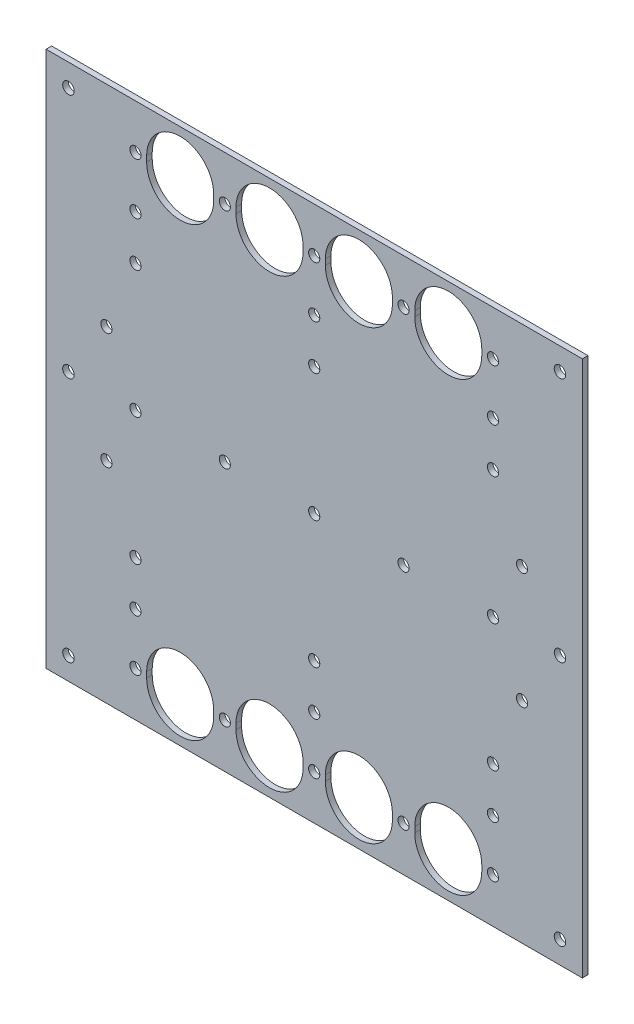
SolidWorks part; units mm, degrees
ref_plane "Front Plane" through (0, 0, 0) normal (0, 0, 1) x (1, 0, 0)
ref_plane "Top Plane" through (0, 0, 0) normal (0, 1, 0) x (1, 0, 0)
ref_plane "Right Plane" through (0, 0, 0) normal (1, 0, 0) x (0, 0, -1)
sketch "Sketch1" plane through (0, 0, 0) normal (0, 0, 1) x (1, 0, 0)
  line L0 (-152.4, 127) -> (-76.2, 127) construction
  line L1 (-152.4, 152.4) -> (152.4, 152.4)
  line L2 (-152.4, 152.4) -> (-152.4, -152.4)
  line L3 (-152.4, -152.4) -> (152.4, -152.4)
  line L4 (152.4, 152.4) -> (152.4, -152.4)
  line L5 (-76.2, 127) -> (-25.4, 127) construction
  line L6 (-25.4, 127) -> (25.4, 127) construction
  line L7 (25.4, 127) -> (76.2, 127) construction
  line L8 (76.2, 127) -> (152.4, 127) construction
  line L9 (-152.4, 0) -> (152.4, 0) construction
  line L10 (0, 152.4) -> (0, -152.4) construction
  line L11 (-118.11, 152.4) -> (-118.11, -152.4) construction
  line L12 (-152.4, -127) -> (152.4, -127) construction
  line L13 (127, 152.4) -> (127, -152.4) construction
  line L14 (-50.8, 152.4) -> (-50.8, -152.4) construction
  line L15 (50.8, 152.4) -> (50.8, -152.4) construction
  line L16 (-101.6, 152.4) -> (-101.6, -152.4) construction
  line L17 (-95.25, 66.04) -> (-57.15, 66.04) construction
  line L18 (-95.25, 66.04) -> (-95.25, -66.04) construction
  line L19 (-95.25, -66.04) -> (-57.15, -66.04) construction
  line L20 (-57.15, 66.04) -> (-57.15, -66.04) construction
  line L21 (-44.45, 66.04) -> (-6.35, 66.04) construction
  line L22 (-44.45, 66.04) -> (-44.45, -66.04) construction
  line L23 (-44.45, -66.04) -> (-6.35, -66.04) construction
  line L24 (-6.35, 66.04) -> (-6.35, -66.04) construction
  line L25 (6.35, 66.04) -> (44.45, 66.04) construction
  line L26 (6.35, 66.04) -> (6.35, -66.04) construction
  line L27 (6.35, -66.04) -> (44.45, -66.04) construction
  line L28 (44.45, 66.04) -> (44.45, -66.04) construction
  line L29 (57.15, 66.04) -> (95.25, 66.04) construction
  line L30 (57.15, 66.04) -> (57.15, -66.04) construction
  line L31 (57.15, -66.04) -> (95.25, -66.04) construction
  line L32 (95.25, 66.04) -> (95.25, -66.04) construction
  line L33 (101.6, 152.4) -> (101.6, -152.4) construction
  line L34 (-152.4, 120.65) -> (152.4, 120.65) construction
  line L35 (-101.6, 39.7057) -> (-95.25, 39.7057) construction
  line L36 (-57.15, 39.7057) -> (-50.8, 39.7057) construction
  line L37 (-76.2, 66.04) -> (-76.2, 0) construction
  line L38 (-76.2, 0) -> (-76.2, -66.04) construction
  line L39 (-152.4, 72.39) -> (152.4, 72.39) construction
  line L40 (-152.4, -72.39) -> (152.4, -72.39) construction
  line L41 (-76.2, 66.04) -> (-76.2, 72.39) construction
  line L42 (-95.25, -66.04) -> (-95.25, -72.39) construction
  line L43 (95.25, 39.7057) -> (101.6, 39.7057) construction
  line L44 (-95.25, 111.76) -> (-57.15, 111.76) construction
  line L45 (-57.15, 111.76) -> (-57.15, 118.4779) construction
  line L46 (-94.0266, 120.65) -> (-78.1749, 130.2582) construction
  line L47 (-95.25, 111.76) -> (-95.25, 118.4779) construction
  line L48 (-58.3734, 120.65) -> (-74.2251, 130.2582) construction
  line L49 (-107.3169, 130.81) -> (-83.1894, 130.81) construction
  line L50 (-6.35, 111.76) -> (-6.35, 118.4779) construction
  line L51 (-7.5734, 120.65) -> (-23.4251, 130.2582) construction
  line L52 (-43.2266, 120.65) -> (-27.3749, 130.2582) construction
  line L53 (-44.45, 111.76) -> (-44.45, 118.4779) construction
  line L54 (-6.35, 111.76) -> (-44.45, 111.76) construction
  line L55 (44.45, 111.76) -> (44.45, 118.4779) construction
  line L56 (43.2266, 120.65) -> (27.3749, 130.2582) construction
  line L57 (7.5734, 120.65) -> (23.4251, 130.2582) construction
  line L58 (6.35, 111.76) -> (6.35, 118.4779) construction
  line L59 (6.35, 111.76) -> (44.45, 111.76) construction
  line L60 (95.25, 111.76) -> (57.15, 111.76) construction
  line L61 (95.25, 111.76) -> (95.25, 118.4779) construction
  line L62 (94.0266, 120.65) -> (78.1749, 130.2582) construction
  line L63 (58.3734, 120.65) -> (74.2251, 130.2582) construction
  line L64 (57.15, 111.76) -> (57.15, 118.4779) construction
  line L65 (-95.25, -111.76) -> (-95.25, -118.4779) construction
  line L66 (-94.0266, -120.65) -> (-78.1749, -130.2582) construction
  line L67 (-58.3734, -120.65) -> (-74.2251, -130.2582) construction
  line L68 (-95.25, -111.76) -> (-57.15, -111.76) construction
  line L69 (-57.15, -111.76) -> (-57.15, -118.4779) construction
  line L70 (-44.45, -111.76) -> (-44.45, -118.4779) construction
  line L71 (-43.2266, -120.65) -> (-27.3749, -130.2582) construction
  line L72 (-6.35, -111.76) -> (-44.45, -111.76) construction
  line L73 (-7.5734, -120.65) -> (-23.4251, -130.2582) construction
  line L74 (-6.35, -111.76) -> (-6.35, -118.4779) construction
  line L75 (6.35, -111.76) -> (6.35, -118.4779) construction
  line L76 (7.5734, -120.65) -> (23.4251, -130.2582) construction
  line L77 (43.2266, -120.65) -> (27.3749, -130.2582) construction
  line L78 (6.35, -111.76) -> (44.45, -111.76) construction
  line L79 (44.45, -111.76) -> (44.45, -118.4779) construction
  line L80 (57.15, -111.76) -> (57.15, -118.4779) construction
  line L81 (58.3734, -120.65) -> (74.2251, -130.2582) construction
  line L82 (94.0266, -120.65) -> (78.1749, -130.2582) construction
  line L83 (95.25, -111.76) -> (57.15, -111.76) construction
  line L84 (95.25, -111.76) -> (95.25, -118.4779) construction
  line L85 (-152.4, 97.79) -> (152.4, 97.79) construction
  line L86 (-50.8, 39.7057) -> (-44.45, 39.7057) construction
  line L87 (-127, 152.4) -> (-127, -152.4) construction
  line L89 (-95.25, 101.6) -> (-92.3192, 101.6) construction
  line L90 (-95.25, 101.6) -> (-95.25, -101.6) construction
  line L96 (-90.8538, 101.6) -> (-90.8538, 68.58) construction
  line L97 (-89.3885, 101.6) -> (-89.3885, 68.58) construction
  line L98 (-92.3192, 101.6) -> (-92.3192, 68.58) construction
  line L99 (-83.5269, 101.6) -> (-83.5269, 68.58) construction
  line L100 (-86.4577, 101.6) -> (-86.4577, 68.58) construction
  line L101 (-89.3885, 101.6) -> (-86.4577, 101.6) construction
  line L102 (-77.6654, 101.6) -> (-77.6654, 68.58) construction
  line L103 (-80.5962, 101.6) -> (-80.5962, 68.58) construction
  line L104 (-83.5269, 101.6) -> (-80.5962, 101.6) construction
  line L105 (-71.8038, 101.6) -> (-71.8038, 68.58) construction
  line L106 (-74.7346, 101.6) -> (-74.7346, 68.58) construction
  line L107 (-77.6654, 101.6) -> (-74.7346, 101.6) construction
  line L108 (-65.9423, 101.6) -> (-65.9423, 68.58) construction
  line L109 (-68.8731, 101.6) -> (-68.8731, 68.58) construction
  line L110 (-71.8038, 101.6) -> (-68.8731, 101.6) construction
  line L111 (-60.0808, 101.6) -> (-60.0808, 68.58) construction
  line L112 (-63.0115, 101.6) -> (-63.0115, 68.58) construction
  line L113 (-65.9423, 101.6) -> (-63.0115, 101.6) construction
  line L114 (-57.15, -101.6) -> (-57.15, 101.6) construction
  line L115 (-60.0808, 101.6) -> (-57.15, 101.6) construction
  line L116 (-92.3192, 68.58) -> (-89.3885, 68.58) construction
  line L117 (-60.0808, -101.6) -> (-57.15, -101.6) construction
  line L118 (-60.0808, -101.6) -> (-60.0808, -68.58) construction
  line L119 (-63.0115, -101.6) -> (-63.0115, -68.58) construction
  line L120 (-65.9423, -101.6) -> (-65.9423, -68.58) construction
  line L121 (-65.9423, -101.6) -> (-63.0115, -101.6) construction
  line L122 (-68.8731, -101.6) -> (-68.8731, -68.58) construction
  line L123 (-71.8038, -101.6) -> (-68.8731, -101.6) construction
  line L124 (-71.8038, -101.6) -> (-71.8038, -68.58) construction
  line L125 (-74.7346, -101.6) -> (-74.7346, -68.58) construction
  line L126 (-77.6654, -101.6) -> (-74.7346, -101.6) construction
  line L127 (-77.6654, -101.6) -> (-77.6654, -68.58) construction
  line L128 (-80.5962, -101.6) -> (-80.5962, -68.58) construction
  line L129 (-83.5269, -101.6) -> (-80.5962, -101.6) construction
  line L130 (-83.5269, -101.6) -> (-83.5269, -68.58) construction
  line L131 (-86.4577, -101.6) -> (-86.4577, -68.58) construction
  line L132 (-89.3885, -101.6) -> (-86.4577, -101.6) construction
  line L133 (-89.3885, -101.6) -> (-89.3885, -68.58) construction
  line L134 (-92.3192, -101.6) -> (-92.3192, -68.58) construction
  line L135 (-95.25, -101.6) -> (-92.3192, -101.6) construction
  line L136 (-9.2808, 68.58) -> (-12.2115, 68.58) construction
  line L137 (6.35, 66.04) -> (44.45, 66.04) construction
  line L138 (-6.35, -66.04) -> (-6.35, -72.39) construction
  line L139 (-25.4, 66.04) -> (-25.4, 72.39) construction
  line L140 (-25.4, 0) -> (-25.4, -66.04) construction
  line L141 (-25.4, 66.04) -> (-25.4, 0) construction
  line L142 (-44.45, 66.04) -> (-44.45, -66.04) construction
  line L143 (-6.35, -66.04) -> (-44.45, -66.04) construction
  line L144 (-6.35, 66.04) -> (-6.35, -66.04) construction
  line L145 (-6.35, 66.04) -> (-44.45, 66.04) construction
  line L146 (-6.35, -101.6) -> (-9.2808, -101.6) construction
  line L147 (-9.2808, -101.6) -> (-9.2808, -68.58) construction
  line L148 (-12.2115, -101.6) -> (-12.2115, -68.58) construction
  line L149 (-12.2115, -101.6) -> (-15.1423, -101.6) construction
  line L150 (-15.1423, -101.6) -> (-15.1423, -68.58) construction
  line L151 (-18.0731, -101.6) -> (-18.0731, -68.58) construction
  line L152 (-18.0731, -101.6) -> (-21.0038, -101.6) construction
  line L153 (-21.0038, -101.6) -> (-21.0038, -68.58) construction
  line L154 (-23.9346, -101.6) -> (-23.9346, -68.58) construction
  line L155 (-23.9346, -101.6) -> (-26.8654, -101.6) construction
  line L156 (-26.8654, -101.6) -> (-26.8654, -68.58) construction
  line L157 (-29.7962, -101.6) -> (-29.7962, -68.58) construction
  line L158 (-29.7962, -101.6) -> (-32.7269, -101.6) construction
  line L159 (-32.7269, -101.6) -> (-32.7269, -68.58) construction
  line L160 (-35.6577, -101.6) -> (-38.5885, -101.6) construction
  line L161 (-35.6577, -101.6) -> (-35.6577, -68.58) construction
  line L162 (-38.5885, -101.6) -> (-38.5885, -68.58) construction
  line L163 (-41.5192, -101.6) -> (-41.5192, -68.58) construction
  line L164 (-41.5192, -101.6) -> (-44.45, -101.6) construction
  line L165 (-41.5192, 101.6) -> (-44.45, 101.6) construction
  line L166 (-44.45, -101.6) -> (-44.45, 101.6) construction
  line L167 (-35.6577, 101.6) -> (-38.5885, 101.6) construction
  line L168 (-38.5885, 101.6) -> (-38.5885, 68.58) construction
  line L169 (-41.5192, 101.6) -> (-41.5192, 68.58) construction
  line L170 (-29.7962, 101.6) -> (-32.7269, 101.6) construction
  line L171 (-32.7269, 101.6) -> (-32.7269, 68.58) construction
  line L172 (-35.6577, 101.6) -> (-35.6577, 68.58) construction
  line L173 (-23.9346, 101.6) -> (-26.8654, 101.6) construction
  line L174 (-26.8654, 101.6) -> (-26.8654, 68.58) construction
  line L175 (-29.7962, 101.6) -> (-29.7962, 68.58) construction
  line L176 (-18.0731, 101.6) -> (-21.0038, 101.6) construction
  line L177 (-21.0038, 101.6) -> (-21.0038, 68.58) construction
  line L178 (-23.9346, 101.6) -> (-23.9346, 68.58) construction
  line L179 (-12.2115, 101.6) -> (-15.1423, 101.6) construction
  line L180 (-15.1423, 101.6) -> (-15.1423, 68.58) construction
  line L181 (-18.0731, 101.6) -> (-18.0731, 68.58) construction
  line L182 (-9.2808, 101.6) -> (-9.2808, 68.58) construction
  line L183 (-12.2115, 101.6) -> (-12.2115, 68.58) construction
  line L184 (-6.35, 101.6) -> (-6.35, -101.6) construction
  line L185 (-6.35, 101.6) -> (-9.2808, 101.6) construction
  line L186 (6.35, 66.04) -> (6.35, -66.04) construction
  line L187 (6.35, -66.04) -> (44.45, -66.04) construction
  line L188 (44.45, 66.04) -> (44.45, -66.04) construction
  line L189 (25.4, 66.04) -> (25.4, 0) construction
  line L190 (25.4, 0) -> (25.4, -66.04) construction
  line L191 (25.4, 66.04) -> (25.4, 72.39) construction
  line L192 (6.35, -66.04) -> (6.35, -72.39) construction
  line L193 (9.2808, 68.58) -> (12.2115, 68.58) construction
  line L194 (6.35, 66.04) -> (6.35, -66.04) construction
  line L195 (44.45, -66.04) -> (6.35, -66.04) construction
  line L196 (44.45, 66.04) -> (44.45, -66.04) construction
  line L197 (44.45, 66.04) -> (6.35, 66.04) construction
  line L198 (6.35, 101.6) -> (9.2808, 101.6) construction
  line L199 (6.35, 101.6) -> (6.35, -101.6) construction
  line L200 (12.2115, 101.6) -> (12.2115, 68.58) construction
  line L201 (9.2808, 101.6) -> (9.2808, 68.58) construction
  line L202 (18.0731, 101.6) -> (18.0731, 68.58) construction
  line L203 (15.1423, 101.6) -> (15.1423, 68.58) construction
  line L204 (12.2115, 101.6) -> (15.1423, 101.6) construction
  line L205 (23.9346, 101.6) -> (23.9346, 68.58) construction
  line L206 (21.0038, 101.6) -> (21.0038, 68.58) construction
  line L207 (18.0731, 101.6) -> (21.0038, 101.6) construction
  line L208 (29.7962, 101.6) -> (29.7962, 68.58) construction
  line L209 (26.8654, 101.6) -> (26.8654, 68.58) construction
  line L210 (23.9346, 101.6) -> (26.8654, 101.6) construction
  line L211 (35.6577, 101.6) -> (35.6577, 68.58) construction
  line L212 (32.7269, 101.6) -> (32.7269, 68.58) construction
  line L213 (29.7962, 101.6) -> (32.7269, 101.6) construction
  line L214 (41.5192, 101.6) -> (41.5192, 68.58) construction
  line L215 (38.5885, 101.6) -> (38.5885, 68.58) construction
  line L216 (35.6577, 101.6) -> (38.5885, 101.6) construction
  line L217 (44.45, -101.6) -> (44.45, 101.6) construction
  line L218 (41.5192, 101.6) -> (44.45, 101.6) construction
  line L219 (41.5192, -101.6) -> (44.45, -101.6) construction
  line L220 (41.5192, -101.6) -> (41.5192, -68.58) construction
  line L221 (38.5885, -101.6) -> (38.5885, -68.58) construction
  line L222 (35.6577, -101.6) -> (35.6577, -68.58) construction
  line L223 (35.6577, -101.6) -> (38.5885, -101.6) construction
  line L224 (32.7269, -101.6) -> (32.7269, -68.58) construction
  line L225 (29.7962, -101.6) -> (32.7269, -101.6) construction
  line L226 (29.7962, -101.6) -> (29.7962, -68.58) construction
  line L227 (26.8654, -101.6) -> (26.8654, -68.58) construction
  line L228 (23.9346, -101.6) -> (26.8654, -101.6) construction
  line L229 (23.9346, -101.6) -> (23.9346, -68.58) construction
  line L230 (21.0038, -101.6) -> (21.0038, -68.58) construction
  line L231 (18.0731, -101.6) -> (21.0038, -101.6) construction
  line L232 (18.0731, -101.6) -> (18.0731, -68.58) construction
  line L233 (15.1423, -101.6) -> (15.1423, -68.58) construction
  line L234 (12.2115, -101.6) -> (15.1423, -101.6) construction
  line L235 (12.2115, -101.6) -> (12.2115, -68.58) construction
  line L236 (9.2808, -101.6) -> (9.2808, -68.58) construction
  line L237 (6.35, -101.6) -> (9.2808, -101.6) construction
  line L238 (57.15, 66.04) -> (95.25, 66.04) construction
  line L239 (57.15, 66.04) -> (57.15, -66.04) construction
  line L240 (57.15, -66.04) -> (95.25, -66.04) construction
  line L241 (95.25, 66.04) -> (95.25, -66.04) construction
  line L242 (92.3192, 68.58) -> (89.3885, 68.58) construction
  line L243 (95.25, -66.04) -> (95.25, -72.39) construction
  line L244 (76.2, 66.04) -> (76.2, 72.39) construction
  line L245 (76.2, 0) -> (76.2, -66.04) construction
  line L246 (76.2, 66.04) -> (76.2, 0) construction
  line L247 (57.15, 66.04) -> (57.15, -66.04) construction
  line L248 (95.25, -66.04) -> (57.15, -66.04) construction
  line L249 (95.25, 66.04) -> (95.25, -66.04) construction
  line L250 (95.25, 66.04) -> (57.15, 66.04) construction
  line L251 (57.15, 66.04) -> (57.15, -66.04) construction
  line L252 (95.25, -66.04) -> (57.15, -66.04) construction
  line L253 (95.25, 66.04) -> (95.25, -66.04) construction
  line L254 (95.25, 66.04) -> (57.15, 66.04) construction
  line L255 (95.25, -101.6) -> (92.3192, -101.6) construction
  line L256 (92.3192, -101.6) -> (92.3192, -68.58) construction
  line L257 (89.3885, -101.6) -> (89.3885, -68.58) construction
  line L258 (89.3885, -101.6) -> (86.4577, -101.6) construction
  line L259 (86.4577, -101.6) -> (86.4577, -68.58) construction
  line L260 (83.5269, -101.6) -> (83.5269, -68.58) construction
  line L261 (83.5269, -101.6) -> (80.5962, -101.6) construction
  line L262 (80.5962, -101.6) -> (80.5962, -68.58) construction
  line L263 (77.6654, -101.6) -> (77.6654, -68.58) construction
  line L264 (77.6654, -101.6) -> (74.7346, -101.6) construction
  line L265 (74.7346, -101.6) -> (74.7346, -68.58) construction
  line L266 (71.8038, -101.6) -> (71.8038, -68.58) construction
  line L267 (71.8038, -101.6) -> (68.8731, -101.6) construction
  line L268 (68.8731, -101.6) -> (68.8731, -68.58) construction
  line L269 (65.9423, -101.6) -> (63.0115, -101.6) construction
  line L270 (65.9423, -101.6) -> (65.9423, -68.58) construction
  line L271 (63.0115, -101.6) -> (63.0115, -68.58) construction
  line L272 (60.0808, -101.6) -> (60.0808, -68.58) construction
  line L273 (60.0808, -101.6) -> (57.15, -101.6) construction
  line L274 (60.0808, 101.6) -> (57.15, 101.6) construction
  line L275 (57.15, -101.6) -> (57.15, 101.6) construction
  line L276 (65.9423, 101.6) -> (63.0115, 101.6) construction
  line L277 (63.0115, 101.6) -> (63.0115, 68.58) construction
  line L278 (60.0808, 101.6) -> (60.0808, 68.58) construction
  line L279 (71.8038, 101.6) -> (68.8731, 101.6) construction
  line L280 (68.8731, 101.6) -> (68.8731, 68.58) construction
  line L281 (65.9423, 101.6) -> (65.9423, 68.58) construction
  line L282 (77.6654, 101.6) -> (74.7346, 101.6) construction
  line L283 (74.7346, 101.6) -> (74.7346, 68.58) construction
  line L284 (71.8038, 101.6) -> (71.8038, 68.58) construction
  line L285 (83.5269, 101.6) -> (80.5962, 101.6) construction
  line L286 (80.5962, 101.6) -> (80.5962, 68.58) construction
  line L287 (77.6654, 101.6) -> (77.6654, 68.58) construction
  line L288 (89.3885, 101.6) -> (86.4577, 101.6) construction
  line L289 (86.4577, 101.6) -> (86.4577, 68.58) construction
  line L290 (83.5269, 101.6) -> (83.5269, 68.58) construction
  line L291 (92.3192, 101.6) -> (92.3192, 68.58) construction
  line L292 (89.3885, 101.6) -> (89.3885, 68.58) construction
  line L293 (95.25, 101.6) -> (95.25, -101.6) construction
  line L294 (95.25, 101.6) -> (92.3192, 101.6) construction
  line L295 (-101.6, 39.7057) -> (-107.95, 39.7057) construction
  line L296 (-101.6, 78.74) -> (101.6, 78.74) construction
  line L297 (-107.95, 72.39) -> (-107.95, -72.39) construction
  line L298 (-101.6, -78.74) -> (101.6, -78.74) construction
  line L299 (107.95, 72.39) -> (107.95, -72.39) construction
  line L300 (-97.0611, 78.74) -> (-97.0611, 72.39) construction
  line L301 (-107.95, 22.225) -> (-120.65, 22.225) construction
  line L302 (-127, 15.875) -> (-127, -15.875) construction
  line L303 (-120.65, -22.225) -> (-107.95, -22.225) construction
  line L304 (-76.2, 125.4125) -> (-76.2, 128.5875) construction
  line L305 (-95.25, 125.4125) -> (-95.25, 128.5875)
  line L306 (-57.15, 125.4125) -> (-57.15, 128.5875)
  line L307 (-25.4, 125.4125) -> (-25.4, 128.5875) construction
  line L308 (-6.35, 125.4125) -> (-6.35, 128.5875)
  line L309 (-44.45, 125.4125) -> (-44.45, 128.5875)
  line L310 (25.4, 125.4125) -> (25.4, 128.5875) construction
  line L311 (6.35, 125.4125) -> (6.35, 128.5875)
  line L312 (44.45, 125.4125) -> (44.45, 128.5875)
  line L313 (76.2, 125.4125) -> (76.2, 128.5875) construction
  line L314 (95.25, 125.4125) -> (95.25, 128.5875)
  line L315 (57.15, 125.4125) -> (57.15, 128.5875)
  line L316 (-76.2, -125.4125) -> (-76.2, -128.5875) construction
  line L317 (-95.25, -125.4125) -> (-95.25, -128.5875)
  line L318 (-57.15, -125.4125) -> (-57.15, -128.5875)
  line L319 (-25.4, -125.4125) -> (-25.4, -128.5875) construction
  line L320 (-6.35, -125.4125) -> (-6.35, -128.5875)
  line L321 (-44.45, -125.4125) -> (-44.45, -128.5875)
  line L322 (25.4, -125.4125) -> (25.4, -128.5875) construction
  line L323 (6.35, -125.4125) -> (6.35, -128.5875)
  line L324 (44.45, -125.4125) -> (44.45, -128.5875)
  line L325 (76.2, -125.4125) -> (76.2, -128.5875) construction
  line L326 (95.25, -125.4125) -> (95.25, -128.5875)
  line L327 (57.15, -125.4125) -> (57.15, -128.5875)
  circle A4 centre (-101.6, 0) radius 3.175
  circle A5 centre (-50.8, 0) radius 3.175
  circle A6 centre (0, 0) radius 3.175
  circle A7 centre (101.6, 0) radius 3.175
  circle A8 centre (50.8, 0) radius 3.175
  circle A9 centre (-50.8, 127) radius 3.175
  circle A10 centre (0, 127) radius 3.175
  circle A11 centre (50.8, 127) radius 3.175
  circle A12 centre (-101.6, 72.39) radius 3.175
  circle A13 centre (0, 72.39) radius 3.175
  circle A14 centre (101.6, 72.39) radius 3.175
  circle A15 centre (-101.6, -72.39) radius 3.175
  circle A16 centre (0, -72.39) radius 3.175
  circle A17 centre (101.6, -72.39) radius 3.175
  arc A18 (-74.2251, 130.2582) -> (-78.1749, 130.2582) centre (-76.2, 127) ccw construction
  arc A19 (-57.15, 118.4779) -> (-58.3734, 120.65) centre (-59.69, 118.4779) ccw construction
  arc A20 (-95.25, 118.4779) -> (-94.0266, 120.65) centre (-92.71, 118.4779) cw construction
  arc A21 (-6.35, 118.4779) -> (-7.5734, 120.65) centre (-8.89, 118.4779) ccw construction
  arc A22 (-27.3749, 130.2582) -> (-23.4251, 130.2582) centre (-25.4, 127) cw construction
  arc A23 (-44.45, 118.4779) -> (-43.2266, 120.65) centre (-41.91, 118.4779) cw construction
  arc A24 (44.45, 118.4779) -> (43.2266, 120.65) centre (41.91, 118.4779) ccw construction
  arc A25 (27.3749, 130.2582) -> (23.4251, 130.2582) centre (25.4, 127) ccw construction
  arc A26 (6.35, 118.4779) -> (7.5734, 120.65) centre (8.89, 118.4779) cw construction
  arc A27 (95.25, 118.4779) -> (94.0266, 120.65) centre (92.71, 118.4779) ccw construction
  arc A28 (74.2251, 130.2582) -> (78.1749, 130.2582) centre (76.2, 127) cw construction
  arc A29 (57.15, 118.4779) -> (58.3734, 120.65) centre (59.69, 118.4779) cw construction
  arc A34 (-95.25, -118.4779) -> (-94.0266, -120.65) centre (-92.71, -118.4779) ccw construction
  arc A35 (-74.2251, -130.2582) -> (-78.1749, -130.2582) centre (-76.2, -127) cw construction
  arc A36 (-57.15, -118.4779) -> (-58.3734, -120.65) centre (-59.69, -118.4779) cw construction
  arc A37 (-44.45, -118.4779) -> (-43.2266, -120.65) centre (-41.91, -118.4779) ccw construction
  arc A38 (-27.3749, -130.2582) -> (-23.4251, -130.2582) centre (-25.4, -127) ccw construction
  arc A39 (-6.35, -118.4779) -> (-7.5734, -120.65) centre (-8.89, -118.4779) cw construction
  arc A40 (6.35, -118.4779) -> (7.5734, -120.65) centre (8.89, -118.4779) ccw construction
  arc A41 (27.3749, -130.2582) -> (23.4251, -130.2582) centre (25.4, -127) cw construction
  arc A42 (44.45, -118.4779) -> (43.2266, -120.65) centre (41.91, -118.4779) cw construction
  arc A43 (57.15, -118.4779) -> (58.3734, -120.65) centre (59.69, -118.4779) ccw construction
  arc A44 (74.2251, -130.2582) -> (78.1749, -130.2582) centre (76.2, -127) ccw construction
  arc A45 (95.25, -118.4779) -> (94.0266, -120.65) centre (92.71, -118.4779) cw construction
  circle A46 centre (50.8, -127) radius 3.175
  circle A47 centre (0, -127) radius 3.175
  circle A48 centre (-50.8, -127) radius 3.175
  circle A49 centre (-101.6, 97.79) radius 3.175
  circle A50 centre (0, 97.79) radius 3.175
  circle A51 centre (101.6, 97.79) radius 3.175
  circle A52 centre (101.6, 127) radius 3.175
  circle A53 centre (-101.6, 127) radius 3.175
  circle A54 centre (-118.11, 33.02) radius 3.175
  circle A56 centre (-101.6, -127) radius 3.175
  circle A57 centre (101.6, -127) radius 3.175
  circle A58 centre (101.6, -97.79) radius 3.175
  circle A59 centre (0, -97.79) radius 3.175
  circle A60 centre (-101.6, -97.79) radius 3.175
  circle A61 centre (-118.11, -33.02) radius 3.175
  circle A63 centre (-139.7, 139.7) radius 3.2639
  circle A64 centre (-139.7, 0) radius 3.2639
  circle A65 centre (-139.7, -139.7) radius 3.2639
  circle A66 centre (139.7, -139.7) radius 3.2639
  circle A67 centre (139.7, 0) radius 3.2639
  circle A68 centre (139.7, 139.7) radius 3.2639
  arc A70 (-92.3192, 68.58) -> (-89.3885, 68.58) centre (-90.8538, 68.58) ccw construction
  arc A71 (-86.4577, 68.58) -> (-83.5269, 68.58) centre (-84.9923, 68.58) ccw construction
  arc A72 (-80.5962, 68.58) -> (-77.6654, 68.58) centre (-79.1308, 68.58) ccw construction
  arc A73 (-74.7346, 68.58) -> (-71.8038, 68.58) centre (-73.2692, 68.58) ccw construction
  arc A74 (-68.8731, 68.58) -> (-65.9423, 68.58) centre (-67.4077, 68.58) ccw construction
  arc A75 (-63.0115, 68.58) -> (-60.0808, 68.58) centre (-61.5462, 68.58) ccw construction
  arc A76 (-63.0115, -68.58) -> (-60.0808, -68.58) centre (-61.5462, -68.58) cw construction
  arc A77 (-68.8731, -68.58) -> (-65.9423, -68.58) centre (-67.4077, -68.58) cw construction
  arc A78 (-74.7346, -68.58) -> (-71.8038, -68.58) centre (-73.2692, -68.58) cw construction
  arc A79 (-80.5962, -68.58) -> (-77.6654, -68.58) centre (-79.1308, -68.58) cw construction
  arc A80 (-86.4577, -68.58) -> (-83.5269, -68.58) centre (-84.9923, -68.58) cw construction
  arc A81 (-92.3192, -68.58) -> (-89.3885, -68.58) centre (-90.8538, -68.58) cw construction
  arc A82 (-9.2808, -68.58) -> (-12.2115, -68.58) centre (-10.7462, -68.58) ccw construction
  arc A83 (-15.1423, -68.58) -> (-18.0731, -68.58) centre (-16.6077, -68.58) ccw construction
  arc A84 (-21.0038, -68.58) -> (-23.9346, -68.58) centre (-22.4692, -68.58) ccw construction
  arc A85 (-26.8654, -68.58) -> (-29.7962, -68.58) centre (-28.3308, -68.58) ccw construction
  arc A86 (-32.7269, -68.58) -> (-35.6577, -68.58) centre (-34.1923, -68.58) ccw construction
  arc A87 (-38.5885, -68.58) -> (-41.5192, -68.58) centre (-40.0538, -68.58) ccw construction
  arc A88 (-38.5885, 68.58) -> (-41.5192, 68.58) centre (-40.0538, 68.58) cw construction
  arc A89 (-32.7269, 68.58) -> (-35.6577, 68.58) centre (-34.1923, 68.58) cw construction
  arc A90 (-26.8654, 68.58) -> (-29.7962, 68.58) centre (-28.3308, 68.58) cw construction
  arc A91 (-21.0038, 68.58) -> (-23.9346, 68.58) centre (-22.4692, 68.58) cw construction
  arc A92 (-15.1423, 68.58) -> (-18.0731, 68.58) centre (-16.6077, 68.58) cw construction
  arc A93 (-9.2808, 68.58) -> (-12.2115, 68.58) centre (-10.7462, 68.58) cw construction
  arc A94 (9.2808, 68.58) -> (12.2115, 68.58) centre (10.7462, 68.58) ccw construction
  arc A95 (15.1423, 68.58) -> (18.0731, 68.58) centre (16.6077, 68.58) ccw construction
  arc A96 (21.0038, 68.58) -> (23.9346, 68.58) centre (22.4692, 68.58) ccw construction
  arc A97 (26.8654, 68.58) -> (29.7962, 68.58) centre (28.3308, 68.58) ccw construction
  arc A98 (32.7269, 68.58) -> (35.6577, 68.58) centre (34.1923, 68.58) ccw construction
  arc A99 (38.5885, 68.58) -> (41.5192, 68.58) centre (40.0538, 68.58) ccw construction
  arc A100 (38.5885, -68.58) -> (41.5192, -68.58) centre (40.0538, -68.58) cw construction
  arc A101 (32.7269, -68.58) -> (35.6577, -68.58) centre (34.1923, -68.58) cw construction
  arc A102 (26.8654, -68.58) -> (29.7962, -68.58) centre (28.3308, -68.58) cw construction
  arc A103 (21.0038, -68.58) -> (23.9346, -68.58) centre (22.4692, -68.58) cw construction
  arc A104 (15.1423, -68.58) -> (18.0731, -68.58) centre (16.6077, -68.58) cw construction
  arc A105 (9.2808, -68.58) -> (12.2115, -68.58) centre (10.7462, -68.58) cw construction
  arc A106 (92.3192, -68.58) -> (89.3885, -68.58) centre (90.8538, -68.58) ccw construction
  arc A107 (86.4577, -68.58) -> (83.5269, -68.58) centre (84.9923, -68.58) ccw construction
  arc A108 (80.5962, -68.58) -> (77.6654, -68.58) centre (79.1308, -68.58) ccw construction
  arc A109 (74.7346, -68.58) -> (71.8038, -68.58) centre (73.2692, -68.58) ccw construction
  arc A110 (68.8731, -68.58) -> (65.9423, -68.58) centre (67.4077, -68.58) ccw construction
  arc A111 (63.0115, -68.58) -> (60.0808, -68.58) centre (61.5462, -68.58) ccw construction
  arc A112 (63.0115, 68.58) -> (60.0808, 68.58) centre (61.5462, 68.58) cw construction
  arc A113 (68.8731, 68.58) -> (65.9423, 68.58) centre (67.4077, 68.58) cw construction
  arc A114 (74.7346, 68.58) -> (71.8038, 68.58) centre (73.2692, 68.58) cw construction
  arc A115 (80.5962, 68.58) -> (77.6654, 68.58) centre (79.1308, 68.58) cw construction
  arc A116 (86.4577, 68.58) -> (83.5269, 68.58) centre (84.9923, 68.58) cw construction
  arc A117 (92.3192, 68.58) -> (89.3885, 68.58) centre (90.8538, 68.58) cw construction
  arc A118 (-101.6, 78.74) -> (-107.95, 72.39) centre (-101.6, 72.39) ccw construction
  arc A119 (-107.95, -72.39) -> (-101.6, -78.74) centre (-101.6, -72.39) ccw construction
  arc A120 (101.6, 78.74) -> (107.95, 72.39) centre (101.6, 72.39) cw construction
  arc A121 (101.6, -78.74) -> (107.95, -72.39) centre (101.6, -72.39) ccw construction
  arc A122 (-127, -15.875) -> (-120.65, -22.225) centre (-120.65, -15.875) ccw construction
  arc A123 (-120.65, 22.225) -> (-127, 15.875) centre (-120.65, 15.875) ccw construction
  arc A124 (-95.25, 125.4125) -> (-57.15, 125.4125) centre (-76.2, 125.4125) ccw
  arc A125 (-57.15, 128.5875) -> (-95.25, 128.5875) centre (-76.2, 128.5875) ccw
  arc A126 (-6.35, 125.4125) -> (-44.45, 125.4125) centre (-25.4, 125.4125) cw
  arc A127 (-44.45, 128.5875) -> (-6.35, 128.5875) centre (-25.4, 128.5875) cw
  arc A128 (6.35, 125.4125) -> (44.45, 125.4125) centre (25.4, 125.4125) ccw
  arc A129 (44.45, 128.5875) -> (6.35, 128.5875) centre (25.4, 128.5875) ccw
  arc A130 (95.25, 125.4125) -> (57.15, 125.4125) centre (76.2, 125.4125) cw
  arc A131 (57.15, 128.5875) -> (95.25, 128.5875) centre (76.2, 128.5875) cw
  arc A132 (-95.25, -125.4125) -> (-57.15, -125.4125) centre (-76.2, -125.4125) cw
  arc A133 (-57.15, -128.5875) -> (-95.25, -128.5875) centre (-76.2, -128.5875) cw
  arc A134 (-6.35, -125.4125) -> (-44.45, -125.4125) centre (-25.4, -125.4125) ccw
  arc A135 (-44.45, -128.5875) -> (-6.35, -128.5875) centre (-25.4, -128.5875) ccw
  arc A136 (6.35, -125.4125) -> (44.45, -125.4125) centre (25.4, -125.4125) cw
  arc A137 (44.45, -128.5875) -> (6.35, -128.5875) centre (25.4, -128.5875) cw
  arc A138 (95.25, -125.4125) -> (57.15, -125.4125) centre (76.2, -125.4125) ccw
  arc A139 (57.15, -128.5875) -> (95.25, -128.5875) centre (76.2, -128.5875) ccw
  circle A140 centre (118.11, 33.02) radius 3.175
  circle A141 centre (118.11, -33.02) radius 3.175
  point P10 (-76.2, 111.76)
  point P36 (-76.2, 127)
  point P63 (50.8, 127)
  point P95 (-76.2, 66.04)
  point P97 (-25.4, 66.04)
  point P99 (25.4, 66.04)
  point P101 (76.2, 66.04)
  point P116 (-95.25, 0)
  point P118 (-44.45, 0)
  point P119 (6.35, 0)
  point P120 (57.15, 0)
  point P159 (-76.2, 123.031)
  point P162 (-25.4, 127)
  point P219 (-76.2, 33.02)
  point P259 (0, 78.74)
  point P260 (-107.95, 0)
  point P545 (-127, 0)
  point P548 (-127, -22.225)
  point P551 (-127, 22.225)
  point P558 (25.4, 127)
  point P565 (76.2, 127)
  point P572 (-76.2, -127)
  point P579 (-25.4, -127)
  point P586 (25.4, -127)
  point P593 (76.2, -127)
  dimension "D7" = 6.35
  dimension "D11" = 7.62
  dimension "D13" = 2.54
  dimension "D19" = 6.5278
  dimension "D25" = 6.35
  dimension "D26" = 6.35
  dimension "D27" = 6.35
  dimension "D29" = 6.35
  dimension "D2" = 25.4
  dimension "D3" = 50.8
  dimension "D4" = 25.4
  dimension "D5" = 25.4
  dimension "D6" = 25.4
  dimension "D8" = 38.1
  dimension "D9" = 31.75
  dimension "D10" = 132.08
  dimension "D12" = 19.05
  dimension "D14" = 25.4
  dimension "D15" = 304.8
  dimension "D16" = 304.8
  dimension "D17" = 8.89
  dimension "D18" = 12.7
  dimension "D20" = 12.7
  dimension "D21" = 12.7
  dimension "D23" = 33.02
  dimension "D24" = 10.16
  dimension "D28" = 44.45
  dimension "D30" = 38.1
  dimension "D31" = 3.175
  dimension "D22" = 6
extrude "Boss-Extrude1" add sketch "Sketch1" along normal blind 3.175 contours L4 L1 L2 L3 A67 A141 A60 A58 A56 A140 A54 A53 A52 A51 A50 A49 A47 L84 A45 L82 A44 L81 A43 L80 L83 L74 A39 L73 A38 L71 A37 L70 L72 L64 A29
